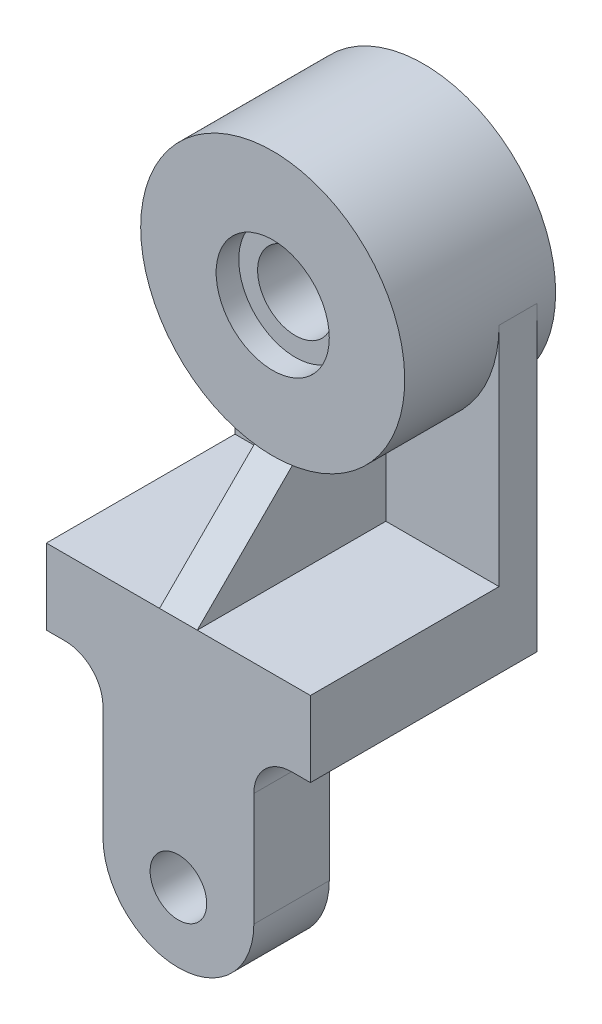
SolidWorks part; units mm, degrees
ref_plane "Front Plane" through (0, 0, 0) normal (0, 0, 1) x (1, 0, 0)
ref_plane "Top Plane" through (0, 0, 0) normal (0, 1, 0) x (1, 0, 0)
ref_plane "Right Plane" through (0, 0, 0) normal (1, 0, 0) x (0, 0, -1)
sketch "Sketch1" plane through (0, 0, 0) normal (0, 1, 0) x (1, 0, 0)
  line L1 (889, -762) -> (-889, -762)
  line L2 (889, -762) -> (889, 762)
  line L3 (889, 762) -> (-889, 762)
  line L4 (-889, -762) -> (-889, 762)
  line L5 (889, -762) -> (-889, 762) construction
  line L6 (889, 762) -> (-889, -762) construction
  point P0 (0, 0)
  dimension "D1" = 1778
  dimension "D2" = 1524
extrude "Boss-Extrude1" add sketch "Sketch1" along normal blind 508 contours L2 L3 L4 L1
sketch "Sketch2" plane through (0, 508, 0) normal (0, 1, 0) x (1, 0, 0)
  line L0 (889, -762) -> (889, 762) construction
  line L1 (-889, 762) -> (889, 762)
  line L2 (-889, 762) -> (-889, 508)
  line L3 (-889, 508) -> (889, 508)
  line L4 (889, 762) -> (889, 508)
  dimension "D1" = 254
extrude "Boss-Extrude2" add sketch "Sketch2" along normal blind 1524
sketch "Sketch3" plane through (0, 0, 762) normal (0, 0, 1) x (1, 0, 0)
  line L0 (0, 508) -> (0, -1016) construction
  line L1 (889, 508) -> (-889, 508) construction
  line L2 (-508, -1016) -> (-508, 0)
  line L3 (889, 0) -> (-889, 0) construction
  line L4 (508, -1016) -> (508, 0)
  line L9 (-889, 0) -> (889, 0)
  line L10 (889, 0) -> (889, 508)
  line L11 (889, 508) -> (-889, 508)
  line L12 (-889, 508) -> (-889, 0)
  line L13 (-508, 0) -> (508, 0)
  arc A0 (-508, -1016) -> (508, -1016) centre (0, -1016) ccw
  dimension "D2" = 1016
  dimension "D1" = 1524
  dimension "D3" = 0
extrude "Boss-Extrude3" add sketch "Sketch3" against normal blind 508
fillet "Fillet1" radius 254 2 edges at (508, 0, 508) (-508, 0, 508)
sketch "Sketch4" plane through (0, 0, 762) normal (0, 0, 1) x (1, 0, 0)
  circle A1 centre (0, -1055.2203) radius 190.5
  dimension "D1" = 381
extrude "Cut-Extrude1" cut sketch "Sketch4" against normal blind 508
sketch "Sketch5" plane through (0, 0, -762) normal (0, 0, -1) x (-1, 0, 0)
  line L0 (-889, 2032) -> (889, 2032) construction
  circle A0 centre (0, 2032) radius 889
extrude "Boss-Extrude4" add sketch "Sketch5" along normal blind 127 and the other way blind 889
sketch "Sketch6" plane through (0, 0, 127) normal (0, 0, 1) x (1, 0, 0)
  circle A0 centre (0, 2022.2596) radius 254
  dimension "D1" = 508
extrude "Cut-Extrude2" cut sketch "Sketch6" against normal through all
sketch "Sketch7" plane through (0, 0, 127) normal (0, 0, 1) x (1, 0, 0)
  circle A0 centre (0, 2022.2596) radius 381
  dimension "D1" = 762
extrude "Cut-Extrude3" cut sketch "Sketch7" against normal blind 152.4
ref_plane "Plane1" through (0, 0, -381) normal (0, 0, 1) x (1, 0, 0)
mirror "Mirror1" about plane through (0, 0, -381) normal (0, 0, 1) of "Cut-Extrude3"
sketch "Sketch8" plane through (0, 0, 0) normal (1, 0, 0) x (0, 0, -1)
  line L0 (-127, 1143) -> (-762, 508)
rib "Rib1" sketch "Sketch8" sketch "Sketch8" thickness 254 extrusion direction parallel to sketch draft on no parameters "D1"=254
